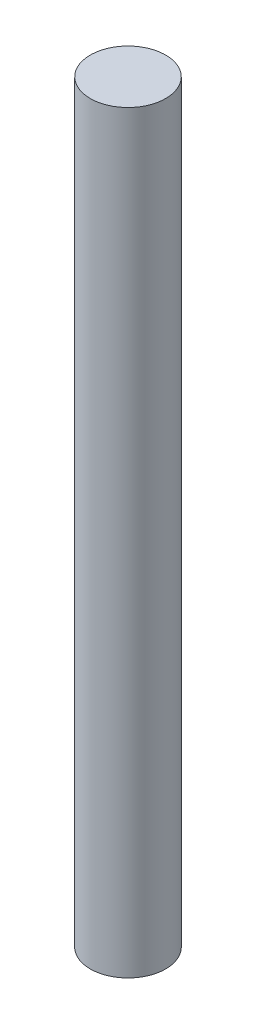
SolidWorks part; units mm, degrees
ref_plane "前基準面" through (0, 0, 0) normal (0, 0, 1) x (1, 0, 0)
ref_plane "上基準面" through (0, 0, 0) normal (0, 1, 0) x (1, 0, 0)
ref_plane "右基準面" through (0, 0, 0) normal (1, 0, 0) x (0, 0, -1)
sketch "草圖1" plane through (0, 0, 0) normal (0, 1, 0) x (1, 0, 0)
  circle A0 centre (0, 0) radius 1.5
  dimension "D1" = 3
extrude "伸長1" add sketch "草圖1" along normal blind 30
